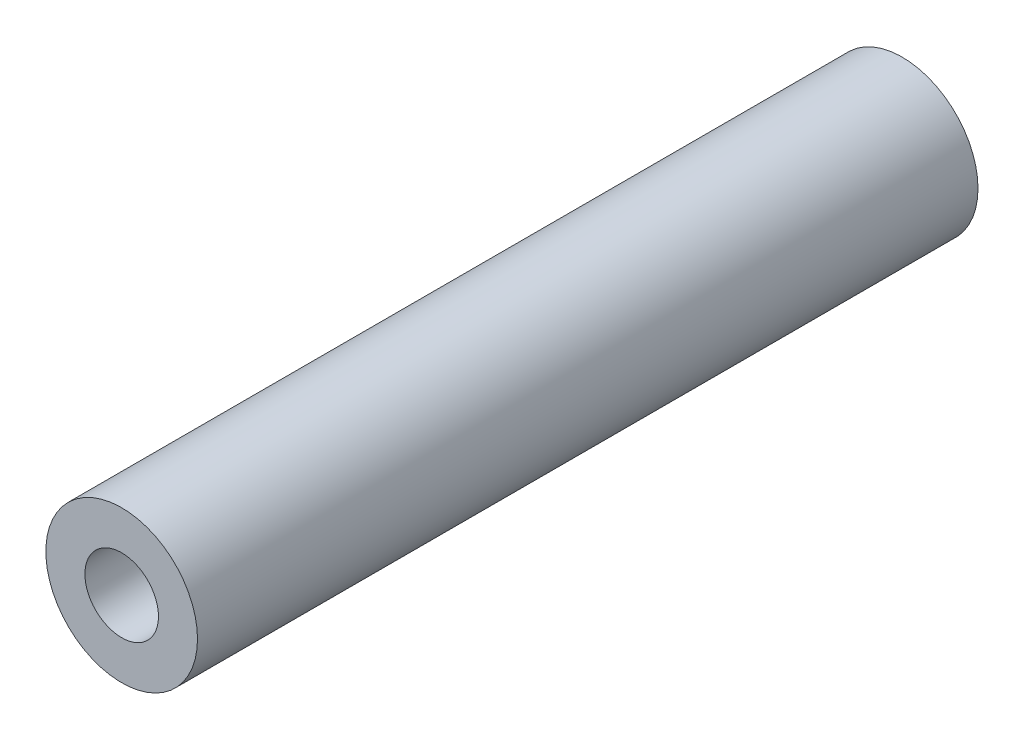
SolidWorks part; units mm, degrees
ref_plane "Front Plane" through (0, 0, 0) normal (0, 0, 1) x (1, 0, 0)
ref_plane "Top Plane" through (0, 0, 0) normal (0, 1, 0) x (1, 0, 0)
ref_plane "Right Plane" through (0, 0, 0) normal (1, 0, 0) x (0, 0, -1)
sketch "M3 sleeve profile" plane through (0, 0, 0) normal (0, 0, 1) x (1, 0, 0)
  circle A0 centre (0, 0) radius 3.4
  circle A1 centre (0, 0) radius 1.65
extrude "M3 sleeve" add sketch "M3 sleeve profile" along normal blind 35
